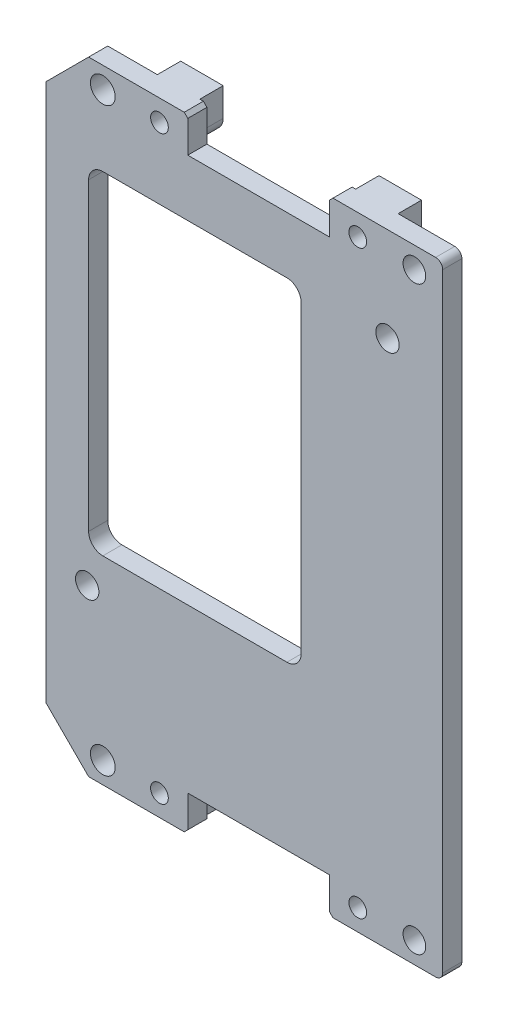
SolidWorks part; units mm, degrees
material "6061 合金"
ref_plane "前视基准面" through (0, 0, 0) normal (0, 0, 1) x (1, 0, 0)
ref_plane "上视基准面" through (0, 0, 0) normal (0, 1, 0) x (1, 0, 0)
ref_plane "右视基准面" through (0, 0, 0) normal (1, 0, 0) x (0, 0, -1)
sketch "草图1" plane through (0, 0, 0) normal (0, 0, 1) x (1, 0, 0)
  line L1 (-28, -44) -> (28, -44)
  line L2 (-28, -44) -> (-28, 44)
  line L3 (-28, 44) -> (28, 44)
  line L4 (28, -44) -> (28, 44)
  line L5 (-28, -44) -> (28, 44) construction
  line L6 (-28, 44) -> (28, -44) construction
  point P0 (0, 0)
  dimension "D1" = 56
  dimension "D2" = 88
extrude "凸台-拉伸1" add sketch "草图1" along normal blind 2.7
fillet "圆角1" radius 1 2 edges at (28, 44, 1.35) (28, -44, 1.35)
sketch "草图8" plane through (0, 0, 0) normal (0, 0, -1) x (-1, 0, 0)
  line L0 (28, 0) -> (-48.8572, 0) construction
  line L1 (28, 44) -> (28, -44) construction
  line L2 (-28, -43) -> (-28, 43) construction
  circle A0 centre (-24, 41) radius 1.6
  circle A1 centre (20, 41) radius 1.75
  circle A2 centre (-24, -41) radius 1.6
  circle A3 centre (20, -41) radius 1.75
  dimension "D1" = 82
  dimension "D2" = 82
  dimension "D3" = 3.5
  dimension "D4" = 3.2
  dimension "D5" = 44
  dimension "D6" = 4
extrude "切除-拉伸1" cut sketch "草图8" against normal blind 10
chamfer "倒角1" distance 6 angle 45 2 edges at (-28, -44, 1.35) (-28, 44, 1.35)
sketch "草图16" plane through (0, 0, 0) normal (0, 0, -1) x (-1, 0, 0)
  circle A0 centre (22.2, -20.7) radius 3
  circle A1 centre (-20.2, 30.7) radius 3
  dimension "D1" = 6
extrude "凸台-拉伸3" add sketch "草图16" along normal blind 1
hole_wizard "M4 螺纹孔1" positions "草图10" profile "草图9" tap size "M4" standard "Iso"
sketch "草图10" plane through (0, 0, 2.7) normal (0, 0, 1) x (1, 0, 0)
  point P0 (20.2, 30.7)
  point P3 (-22.2, -20.7)
sketch "草图9" plane through (20.2, 30.7, 2.7) normal (1, 0, 0) x (0, -1, 0)
  line L0 (0, 0) -> (0, 11.0914)
  line L1 (0, 11.0914) -> (1.65, 10.1)
  line L2 (1.65, 10.1) -> (1.65, 0)
  line L5 (1.65, 0) -> (0, 0)
  line L10 (0, 11.0914) -> (-1.65, 10.1) construction
  line L11 (0, -6.35) -> (0, 107.95) construction
  dimension "螺纹孔钻头直径" = 3.3
  dimension "螺纹孔钻头深度" = 10.1
  dimension "导头角度" = 118
cosmetic thread "孔螺蚊线10" parameters "D1"=3, "D2"=4
cosmetic thread "孔螺蚊线15" parameters "D1"=3, "D2"=4
sketch "草图11" plane through (0, 0, 0) normal (0, 0, -1) x (-1, 0, 0)
  line L0 (-27, 44) -> (22, 44) construction
  line L1 (-19, 44) -> (-13, 44)
  line L2 (-19, 44) -> (-19, 38)
  line L3 (-19, 38) -> (-13, 38)
  line L4 (-13, 44) -> (-13, 38)
  line L5 (22, -44) -> (-27, -44) construction
  line L6 (9, 44) -> (15, 44)
  line L7 (9, 44) -> (9, 38)
  line L8 (9, 38) -> (15, 38)
  line L9 (15, 44) -> (15, 38)
  line L10 (-19, -44) -> (-13, -44)
  line L11 (-19, -44) -> (-19, -38)
  line L12 (-19, -38) -> (-13, -38)
  line L13 (-13, -44) -> (-13, -38)
  line L14 (-28, -43) -> (-28, 43) construction
  line L15 (9, -38) -> (15, -38)
  line L16 (9, -38) -> (9, -44)
  line L17 (9, -44) -> (15, -44)
  line L18 (15, -38) -> (15, -44)
  dimension "D1" = 6
  dimension "D2" = 6
  dimension "D3" = 6
  dimension "D4" = 6
  dimension "D5" = 28
  dimension "D6" = 9
  dimension "D7" = 6
  dimension "D8" = 6
  dimension "D9" = 6
  dimension "D10" = 6
  dimension "D11" = 28
  dimension "D12" = 9
extrude "凸台-拉伸2" add sketch "草图11" along normal blind 3.3
hole_wizard "M3 螺纹孔1" positions "草图13" profile "草图12" tap size "M3" standard "Iso"
sketch "草图13" plane through (0, 0, -3.3) normal (0, 0, -1) x (-1, 0, 0)
  line L0 (-19, 44) -> (-19, 38) construction
  line L1 (-13, 44) -> (-19, 44) construction
  line L2 (15, 44) -> (9, 44) construction
  line L3 (9, 44) -> (9, 38) construction
  line L4 (-19, -44) -> (-13, -44) construction
  line L5 (-19, -38) -> (-19, -44) construction
  line L7 (9, -38) -> (9, -44) construction
  line L8 (9, -44) -> (15, -44) construction
  point P0 (-16, 41)
  point P2 (12, 41)
  point P4 (-16, -41)
  point P6 (12, -41)
  point P9 (-19, 41)
  dimension "D1" = 3
  dimension "D2" = 3
  dimension "D3" = 3
  dimension "D4" = 3
  dimension "D5" = 3
  dimension "D6" = 3
  dimension "D7" = 3
  dimension "D8" = 3
sketch "草图12" plane through (16, 41, -3.3) normal (1, 0, 0) x (0, 1, 0)
  line L0 (0, 0) -> (0, 8.2511)
  line L1 (0, 8.2511) -> (1.25, 7.5)
  line L2 (1.25, 7.5) -> (1.25, 0)
  line L5 (1.25, 0) -> (0, 0)
  line L10 (0, 8.2511) -> (-1.25, 7.5) construction
  line L11 (0, -6.35) -> (0, 107.95) construction
  dimension "螺纹孔钻头直径" = 2.5
  dimension "螺纹孔钻头深度" = 7.5
  dimension "导头角度" = 118
cosmetic thread "孔螺蚊线11" parameters "D1"=6, "D2"=3
cosmetic thread "孔螺蚊线12" parameters "D1"=6, "D2"=3
cosmetic thread "孔螺蚊线13" parameters "D1"=6, "D2"=3
cosmetic thread "孔螺蚊线14" parameters "D1"=6, "D2"=3
sketch "草图14" plane through (0, 0, 0) normal (0, 0, -1) x (-1, 0, 0)
  line L0 (28, 38) -> (28, -38) construction
  line L1 (-8, 31) -> (22, 31)
  line L2 (-8, 31) -> (-8, -16)
  line L3 (-8, -16) -> (22, -16)
  line L4 (22, 31) -> (22, -16)
  line L5 (-13, 44) -> (9, 44) construction
  line L6 (-28, -43) -> (-28, 43) construction
  line L7 (9, -44) -> (-13, -44) construction
  dimension "D1" = 6
  dimension "D2" = 13
  dimension "D3" = 20
  dimension "D4" = 28
extrude "切除-拉伸2" cut sketch "草图14" against normal blind 10
fillet "圆角2" radius 2 4 edges at (-22, -16, 1.35) (8, -16, 1.35) (8, 31, 1.35) (-22, 31, 1.35)
sketch "草图15" plane through (0, -44, 0) normal (0, -1, 0) x (1, 0, 0)
  line L0 (-9, 0) -> (13, 0) construction
  line L1 (12, 0) -> (-8, 0)
  line L2 (12, 0) -> (12, 2.7)
  line L3 (12, 2.7) -> (-8, 2.7)
  line L4 (-8, 0) -> (-8, 2.7)
  line L5 (-22, 2.7) -> (27, 2.7) construction
  line L6 (13, -3.3) -> (13, 0) construction
  line L7 (-9, -3.3) -> (-9, 0) construction
  dimension "D1" = 1
  dimension "D2" = 1
extrude "切除-拉伸3" cut sketch "草图15" against normal blind 5
ref_plane "基准面1" through (0, 0, 0) normal (0, -1, 0) x (-1, 0, 0)
mirror "镜向2" about plane through (0, 0, 0) normal (0, -1, 0) of "切除-拉伸3"
chamfer "倒角2" distance 0.5 angle 45 4 edges at (-8, -44, 1.35) (12, -44, 1.35) (12, 44, 1.35) (-8, 44, 1.35)
fillet "圆角3" radius 2 8 edges at (13, -38, -1.65) (19, -38, -1.65) (-15, -38, -1.65) (-9, -38, -1.65) (13, 38, -1.65) (19, 38, -1.65) (-9, 38, -1.65) (-15, 38, -1.65)
